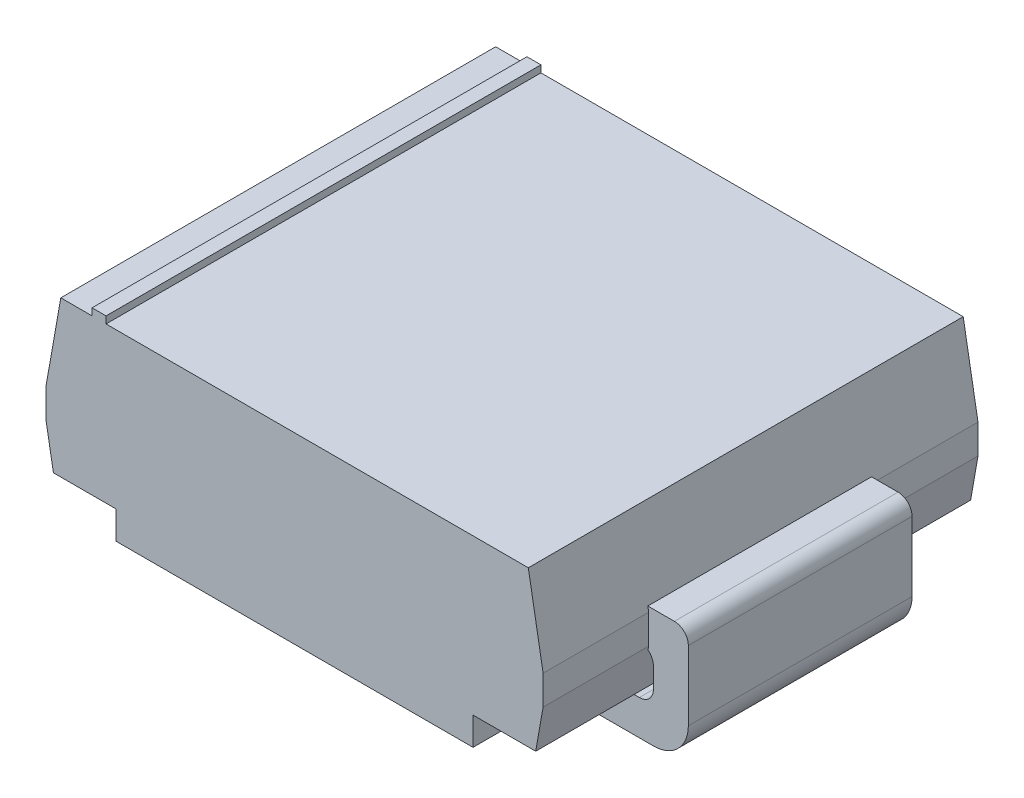
SolidWorks part; units mm, degrees
ref_plane "前视基准面" through (0, 0, 0) normal (0, 0, 1) x (1, 0, 0)
ref_plane "上视基准面" through (0, 0, 0) normal (0, 1, 0) x (1, 0, 0)
ref_plane "右视基准面" through (0, 0, 0) normal (1, 0, 0) x (0, 0, -1)
sketch "草图1" plane through (0, 0, 0) normal (0, 1, 0) x (1, 0, 0)
  line L0 (-6.412, 0) -> (5.5271, 0) construction
  line L1 (-3.555, 3.11) -> (3.555, 3.11)
  line L2 (-3.555, 3.11) -> (-3.555, -3.11)
  line L3 (-3.555, -3.11) -> (3.555, -3.11)
  line L4 (3.555, 3.11) -> (3.555, -3.11)
  line L5 (0, 3.8829) -> (0, -4.6079) construction
  dimension "D1" = 6.22
  dimension "D2" = 7.11
extrude "凸台-拉伸1" add sketch "草图1" along normal blind 2.62
chamfer "倒角1" distance 1.2 angle 10 2 edges at (3.555, 2.62, 0) (-3.555, 2.62, 0)
chamfer "倒角2" distance 1 angle 10 2 edges at (3.555, 0, 0) (-3.555, 0, 0)
sketch "草图3" plane through (0, 0, 3.11) normal (0, 0, 1) x (1, 0, 0)
  line L0 (0, -0.6313) -> (0, 3.9388) construction
  line L1 (-3.3787, 0) -> (3.3787, 0) construction
  line L2 (-2.5529, 0) -> (-4.1425, 0)
  line L3 (-2.5529, 0) -> (-2.5529, 0.4)
  line L4 (-2.5529, 0.4) -> (-4.1425, 0.4)
  line L5 (-4.1425, 0) -> (-4.1425, 0.4)
  line L6 (4.1425, 0) -> (4.1425, 0.4)
  line L7 (2.5529, 0.4) -> (4.1425, 0.4)
  line L8 (2.5529, 0) -> (2.5529, 0.4)
  line L9 (2.5529, 0) -> (4.1425, 0)
  dimension "D1" = 0.4
extrude "切除-拉伸1" cut sketch "草图3" against normal through all
sketch "草图2" plane through (0, 0, 0) normal (0, 0, 1) x (1, 0, 0)
  line L0 (0, 4.0475) -> (0, -1.7916) construction
  line L1 (3.3112, 0.9909) -> (3.3112, 1.4909)
  line L2 (-4.1221, 1.4909) -> (-4.1221, -0.203) construction
  line L3 (-2.5529, 0) -> (2.5529, 0) construction
  line L4 (-3.3112, 0.9909) -> (-3.4221, 0.9909)
  line L5 (-3.6221, 0.7909) -> (-3.6221, 0.497)
  line L6 (-3.4221, 0.297) -> (-2.7116, 0.297)
  line L7 (-2.7116, 0.297) -> (-2.7116, -0.203)
  line L8 (-3.3112, 1.4909) -> (-3.9221, 1.4909)
  line L9 (-4.1221, 1.2909) -> (-4.1221, 0.297)
  line L10 (-3.6221, -0.203) -> (-2.7116, -0.203)
  line L11 (3.6221, -0.203) -> (2.7116, -0.203)
  line L12 (-3.555, 1.4909) -> (-4.1221, 1.4909) construction
  line L13 (-3.555, 0.9909) -> (-3.6221, 0.9909) construction
  line L14 (-3.3112, 0.9909) -> (-3.3112, 1.4909)
  line L15 (-2.7116, 0.297) -> (-2.7116, -0.119) construction
  line L16 (-4.1221, -0.203) -> (-3.2045, -0.203) construction
  line L17 (-3.2045, -0.203) -> (-3.2045, -0.203) construction
  line L18 (4.1221, 1.2909) -> (4.1221, 0.297)
  line L19 (3.3112, 1.4909) -> (3.9221, 1.4909)
  line L20 (2.7116, 0.297) -> (2.7116, -0.203)
  line L21 (3.4221, 0.297) -> (2.7116, 0.297)
  line L22 (3.6221, 0.7909) -> (3.6221, 0.497)
  line L23 (3.3112, 0.9909) -> (3.4221, 0.9909)
  line L24 (-3.6221, 0.9909) -> (-3.6221, 0.297) construction
  line L25 (-3.6221, 0.297) -> (-2.7116, 0.297) construction
  arc A0 (-3.6221, -0.203) -> (-4.1221, 0.297) centre (-3.6221, 0.297) cw
  arc A1 (-4.1221, 1.2909) -> (-3.9221, 1.4909) centre (-3.9221, 1.2909) cw
  arc A2 (-3.6221, 0.7909) -> (-3.4221, 0.9909) centre (-3.4221, 0.7909) cw
  arc A3 (-3.6221, 0.497) -> (-3.4221, 0.297) centre (-3.4221, 0.497) ccw
  arc A4 (3.6221, 0.497) -> (3.4221, 0.297) centre (3.4221, 0.497) cw
  arc A5 (3.6221, 0.7909) -> (3.4221, 0.9909) centre (3.4221, 0.7909) ccw
  arc A6 (4.1221, 1.2909) -> (3.9221, 1.4909) centre (3.9221, 1.2909) ccw
  arc A7 (3.6221, -0.203) -> (4.1221, 0.297) centre (3.6221, 0.297) ccw
  dimension "D3" = 0.5
  dimension "D4" = 0.2
  dimension "D2" = 0.203
  dimension "D1" = 0.5
extrude "凸台-拉伸2" add sketch "草图2" along normal blind 1.6 and the other way blind 1.6
sketch "草图4" plane through (0, 2.62, 0) normal (0, 1, 0) x (1, 0, 0)
  line L0 (3.3434, 3.11) -> (-3.3434, 3.11) construction
  line L1 (-2.8961, 3.11) -> (-2.6961, 3.11)
  line L2 (-2.8961, 3.11) -> (-2.8961, -3.11)
  line L3 (-2.8961, -3.11) -> (-2.6961, -3.11)
  line L4 (-2.6961, 3.11) -> (-2.6961, -3.11)
  line L5 (-3.3434, -3.11) -> (3.3434, -3.11) construction
  dimension "D1" = 0.2
extrude "凸台-拉伸3" add sketch "草图4" along normal blind 0.1
